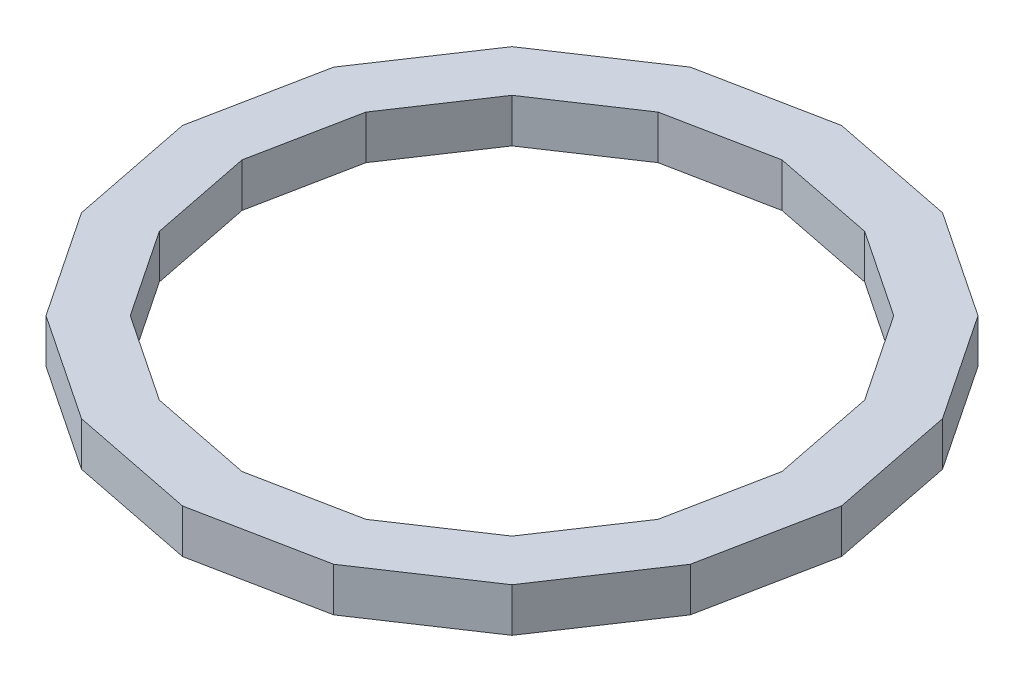
SolidWorks part; units mm, degrees
ref_plane "Front Plane" through (0, 0, 0) normal (0, 0, 1) x (1, 0, 0)
ref_plane "Top Plane" through (0, 0, 0) normal (0, 1, 0) x (1, 0, 0)
ref_plane "Right Plane" through (0, 0, 0) normal (1, 0, 0) x (0, 0, -1)
sketch "Sketch1" plane through (0, 0, 0) normal (0, 1, 0) x (1, 0, 0)
  line L1 (117.3181, 0) -> (108.3878, 44.8957)
  line L2 (108.3878, 44.8957) -> (82.9564, 82.9564)
  line L3 (82.9564, 82.9564) -> (44.8957, 108.3878)
  line L4 (44.8957, 108.3878) -> (0, 117.3181)
  line L5 (0, 117.3181) -> (-44.8957, 108.3878)
  line L6 (-44.8957, 108.3878) -> (-82.9564, 82.9564)
  line L7 (-82.9564, 82.9564) -> (-108.3878, 44.8957)
  line L8 (-108.3878, 44.8957) -> (-117.3181, 0)
  line L9 (-117.3181, 0) -> (-108.3878, -44.8957)
  line L10 (-108.3878, -44.8957) -> (-82.9564, -82.9564)
  line L11 (-82.9564, -82.9564) -> (-44.8957, -108.3878)
  line L12 (-44.8957, -108.3878) -> (0, -117.3181)
  line L13 (0, -117.3181) -> (44.8957, -108.3878)
  line L14 (44.8957, -108.3878) -> (82.9564, -82.9564)
  line L15 (82.9564, -82.9564) -> (108.3878, -44.8957)
  line L16 (108.3878, -44.8957) -> (117.3181, 0)
  line L17 (143.2157, 0) -> (132.3141, 54.8063)
  line L18 (132.3141, 54.8063) -> (101.2688, 101.2688)
  line L19 (101.2688, 101.2688) -> (54.8063, 132.3141)
  line L20 (54.8063, 132.3141) -> (0, 143.2157)
  line L21 (0, 143.2157) -> (-54.8063, 132.3141)
  line L22 (-54.8063, 132.3141) -> (-101.2688, 101.2688)
  line L23 (-101.2688, 101.2688) -> (-132.3141, 54.8063)
  line L24 (-132.3141, 54.8063) -> (-143.2157, 0)
  line L25 (-143.2157, 0) -> (-132.3141, -54.8063)
  line L26 (-132.3141, -54.8063) -> (-101.2688, -101.2688)
  line L27 (-101.2688, -101.2688) -> (-54.8063, -132.3141)
  line L28 (-54.8063, -132.3141) -> (0, -143.2157)
  line L29 (0, -143.2157) -> (54.8063, -132.3141)
  line L30 (54.8063, -132.3141) -> (101.2688, -101.2688)
  line L31 (101.2688, -101.2688) -> (132.3141, -54.8063)
  line L32 (132.3141, -54.8063) -> (143.2157, 0)
  circle A1 centre (0, 0) radius 115.0639 construction
  circle A2 centre (0, 0) radius 140.4639 construction
  dimension "D1" = 25.4
  dimension "D2" = 55.88
extrude "Boss-Extrude1" add sketch "Sketch1" along normal blind 19.05
